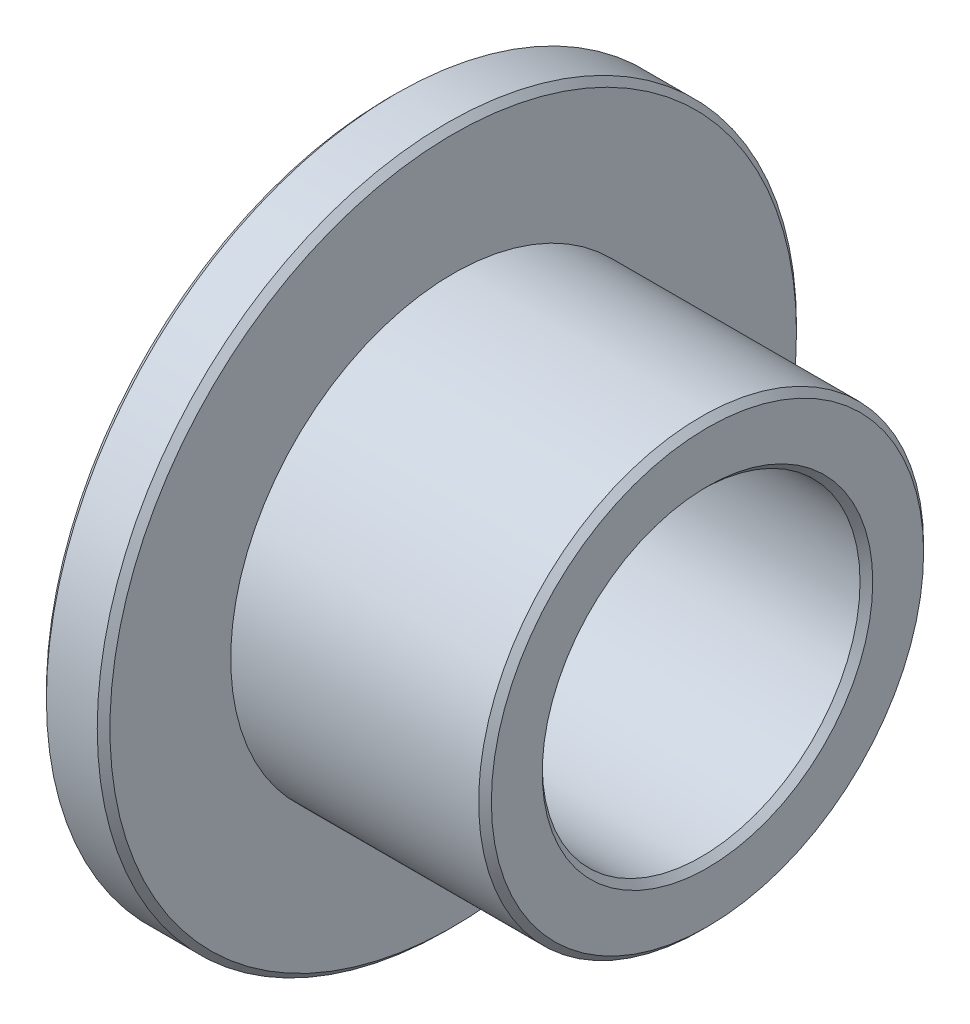
SolidWorks part; units mm, degrees
material "黄铜"
ref_plane "前视基准面" through (0, 0, 0) normal (0, 0, 1) x (1, 0, 0)
ref_plane "上视基准面" through (0, 0, 0) normal (0, 1, 0) x (1, 0, 0)
ref_plane "右视基准面" through (0, 0, 0) normal (1, 0, 0) x (0, 0, -1)
sketch "草图1" plane through (0, 0, 0) normal (1, 0, 0) x (0, 0, -1)
  circle A0 centre (0, 0) radius 11
  dimension "D1" = 22
extrude "凸台-拉伸1" add sketch "草图1" along normal blind 2
sketch "草图2" plane through (2, 0, 0) normal (1, 0, 0) x (0, 0, -1)
  circle A0 centre (0, 0) radius 7
  dimension "D1" = 14
extrude "凸台-拉伸2" add sketch "草图2" along normal blind 8
sketch "草图3" plane through (10, 0, 0) normal (1, 0, 0) x (0, 0, -1)
  circle A0 centre (0, 0) radius 5
  dimension "D1" = 10
extrude "切除-拉伸1" cut sketch "草图3" against normal through all
chamfer "倒角1" distance 0.2 angle 45 5 edges at (10, 0, -5) (10, 0, -7) (2, 0, -11) (0, 0, -11) (0, 0, -5)
